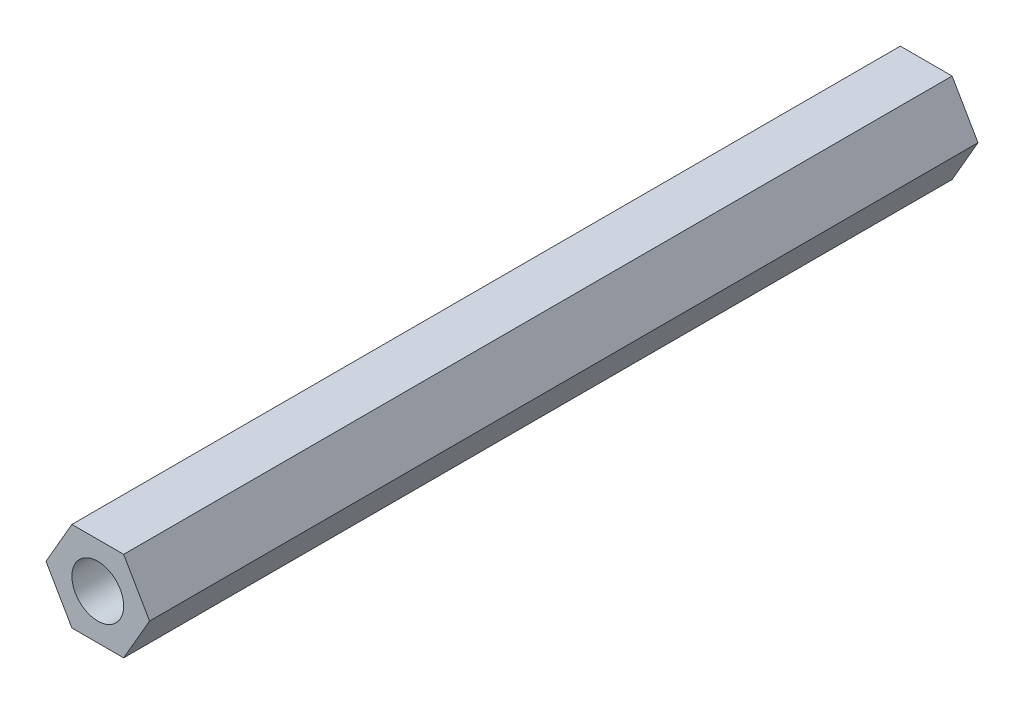
SolidWorks part; units mm, degrees
material "普通碳钢"
ref_plane "前视" through (0, 0, 0) normal (0, 0, 1) x (1, 0, 0)
ref_plane "上视" through (0, 0, 0) normal (0, 1, 0) x (1, 0, 0)
ref_plane "右视" through (0, 0, 0) normal (1, 0, 0) x (0, 0, -1)
sketch "草图1" plane through (0, 0, 0) normal (0, 0, 1) x (1, 0, 0)
  line L0 (0, 0) -> (2.5, 0)
  line L1 (2.5, 0) -> (3.75, -2.1651)
  line L2 (3.75, -2.1651) -> (2.5, -4.3301)
  line L3 (2.5, -4.3301) -> (0, -4.3301)
  line L4 (0, -4.3301) -> (-1.25, -2.1651)
  line L5 (-1.25, -2.1651) -> (0, 0)
  dimension "D1" = 5
  dimension "D2" = 5
extrude "凸台-拉伸1" add sketch "草图1" along normal blind 40
hole_wizard "M3 螺纹孔1" positions "草图3" profile "草图2" tap size "M3" standard "GB" end condition through all
sketch "草图3" plane through (0, 0, 40) normal (0, 0, 1) x (1, 0, 0)
  line L0 (-1.25, -2.1651) -> (3.75, -2.1651) construction
  line L2 (1.25, 0) -> (1.25, -4.3301) construction
  line L3 (2.5, 0) -> (0, 0) construction
  line L4 (0, -4.3301) -> (2.5, -4.3301) construction
  point P0 (1.25, -2.1651)
cosmetic thread "孔螺蚊线1" parameters "D2"=3
sketch "草图2" plane through (1.25, -2.1651, 40) normal (1, 0, 0) x (0, -1, 0)
  line L0 (0, 0) -> (0, 40)
  line L1 (0, 40) -> (1.25, 40)
  line L2 (1.25, 40) -> (1.25, 0)
  line L5 (1.25, 0) -> (0, 0)
  line L11 (0, -6.35) -> (0, 107.95) construction
  dimension "通孔螺纹孔钻头直径" = 2.5
  dimension "通孔螺纹孔钻头深度" = 40
